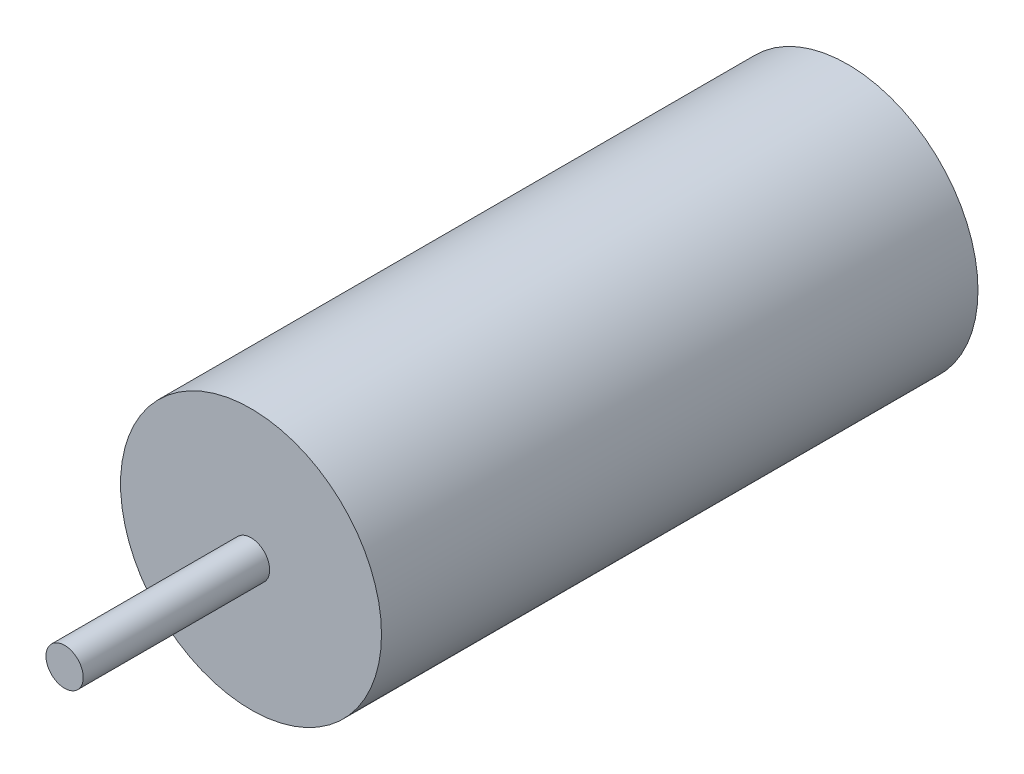
SolidWorks part; units mm, degrees
material "AISI 304"
ref_plane "Front" through (0, 0, 0) normal (0, 0, 1) x (1, 0, 0)
ref_plane "Top" through (0, 0, 0) normal (0, 1, 0) x (1, 0, 0)
ref_plane "Right" through (0, 0, 0) normal (1, 0, 0) x (0, 0, -1)
sketch "草图1" plane through (0, 0, 0) normal (0, 0, 1) x (1, 0, 0)
  circle A0 centre (0, 0) radius 3.5
  dimension "D1" = 7
extrude "凸台-拉伸1" add sketch "草图1" along normal blind 16
sketch "草图2" plane through (0, 0, 16) normal (0, 0, 1) x (1, 0, 0)
  circle A0 centre (0, 0) radius 0.5
  dimension "D1" = 1
extrude "凸台-拉伸2" add sketch "草图2" along normal blind 5
